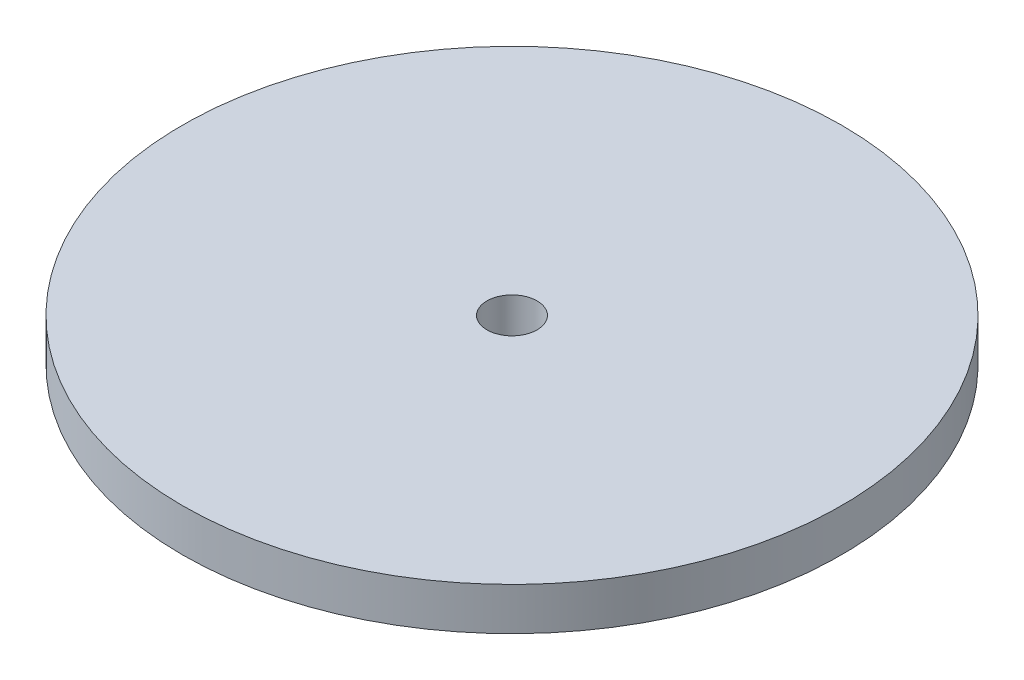
SolidWorks part; units mm, degrees
ref_plane "Front Plane" through (0, 0, 0) normal (0, 0, 1) x (1, 0, 0)
ref_plane "Top Plane" through (0, 0, 0) normal (0, 1, 0) x (1, 0, 0)
ref_plane "Right Plane" through (0, 0, 0) normal (1, 0, 0) x (0, 0, -1)
sketch "Sketch1" plane through (0, 0, 0) normal (0, 0, 1) x (1, 0, 0)
  line L0 (2.794, 0) -> (2.794, 3.3782)
  line L1 (2.794, 3.3782) -> (1.3462, 3.3782)
  line L2 (1.3462, 3.3782) -> (1.3462, 5.6642)
  line L3 (1.3462, 5.6642) -> (17.6657, 5.6642)
  line L4 (17.6657, 5.6642) -> (17.6657, 3.3782)
  line L5 (17.6657, 3.3782) -> (4.3815, 3.3782)
  line L6 (4.3815, 3.3782) -> (4.3815, 0)
  line L7 (4.3815, 0) -> (2.794, 0)
  line L8 (0, 0) -> (0, 13.3005) construction
  dimension "D1" = 1.3462
  dimension "D2" = 2.794
  dimension "D3" = 17.6657
  dimension "D4" = 3.3782
  dimension "D5" = 2.286
  dimension "D6" = 1.5875
revolve "Revolve1" add sketch "Sketch1" angle 360 about L8
